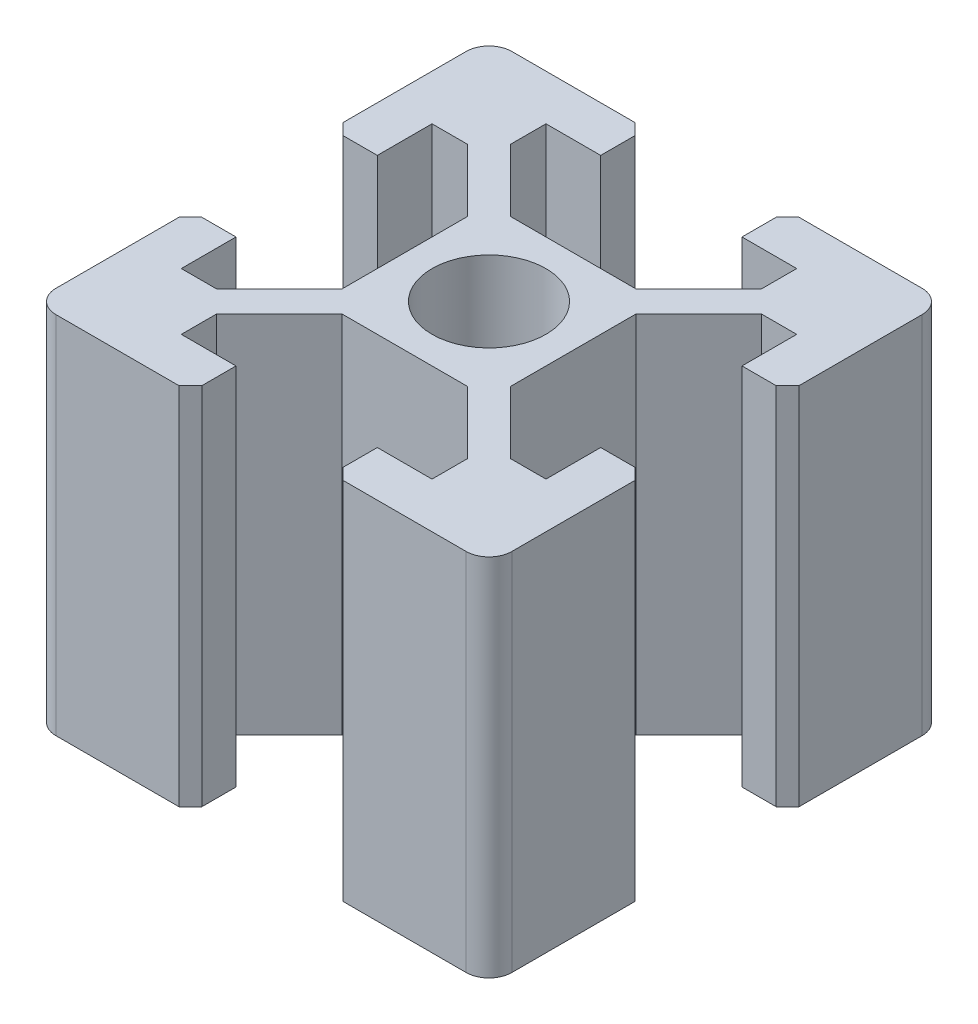
SolidWorks part; units mm, degrees
ref_plane "Front Plane" through (0, 0, 0) normal (0, 0, 1) x (1, 0, 0)
ref_plane "Top Plane" through (0, 0, 0) normal (0, 1, 0) x (1, 0, 0)
ref_plane "Right Plane" through (0, 0, 0) normal (1, 0, 0) x (0, 0, -1)
sketch "Sketch1" plane through (0, 0, 0) normal (0, 1, 0) x (1, 0, 0)
  line L0 (3.6, 10) -> (9, 10)
  line L1 (-9, -10) -> (-3.6, -10)
  line L2 (-10, -9) -> (-10, -3.6)
  line L3 (-9, 10) -> (-3.6, 10)
  line L4 (10, -9) -> (10, -3.6)
  line L5 (-10, -10) -> (10, 10) construction
  line L6 (-10, 10) -> (10, -10) construction
  line L8 (-3.1, 9.5) -> (-3.1, 8)
  line L10 (3.1, 9.5) -> (3.1, 8)
  line L11 (-3.6, 10) -> (-3.1, 9.5)
  line L12 (3.1, 9.5) -> (3.6, 10)
  line L13 (3.1, 8) -> (5.5, 8)
  line L14 (-5.5, 8) -> (-3.1, 8)
  line L15 (-5.5, 8) -> (-5.5, 6.45)
  line L16 (-2.75, 3.7) -> (2.75, 3.7)
  line L17 (5.5, 8) -> (5.5, 6.45)
  line L18 (-5.5, 6.45) -> (-2.75, 3.7)
  line L19 (2.75, 3.7) -> (5.5, 6.45)
  line L20 (3.7, 2.75) -> (6.45, 5.5)
  line L21 (6.45, -5.5) -> (3.7, -2.75)
  line L22 (8, 5.5) -> (6.45, 5.5)
  line L23 (3.7, -2.75) -> (3.7, 2.75)
  line L24 (8, -5.5) -> (6.45, -5.5)
  line L25 (8, -5.5) -> (8, -3.1)
  line L26 (8, 3.1) -> (8, 5.5)
  line L27 (9.5, 3.1) -> (10, 3.6)
  line L28 (10, -3.6) -> (9.5, -3.1)
  line L29 (9.5, 3.1) -> (8, 3.1)
  line L30 (9.5, -3.1) -> (8, -3.1)
  line L31 (10, 3.6) -> (10, 9)
  line L32 (-6.45, 5.5) -> (-3.7, 2.75)
  line L33 (-8, 5.5) -> (-6.45, 5.5)
  line L34 (-8, 5.5) -> (-8, 3.1)
  line L35 (-10, 3.6) -> (-9.5, 3.1)
  line L36 (-9.5, 3.1) -> (-8, 3.1)
  line L37 (-10, 9) -> (-10, 3.6)
  line L38 (3.1, -9.5) -> (3.1, -8)
  line L39 (-3.1, -9.5) -> (-3.1, -8)
  line L40 (3.6, -10) -> (3.1, -9.5)
  line L41 (-3.1, -9.5) -> (-3.6, -10)
  line L42 (5.5, -8) -> (3.1, -8)
  line L43 (5.5, -8) -> (5.5, -6.45)
  line L44 (2.75, -3.7) -> (-2.75, -3.7)
  line L45 (5.5, -6.45) -> (2.75, -3.7)
  line L46 (9, -10) -> (3.6, -10)
  line L47 (-3.6, -10) -> (-10, -10)
  line L48 (-3.1, -8) -> (-5.5, -8)
  line L49 (-5.5, -8) -> (-5.5, -6.45)
  line L50 (-2.75, -3.7) -> (-5.5, -6.45)
  line L51 (-3.7, -2.75) -> (-6.45, -5.5)
  line L52 (-8, -5.5) -> (-6.45, -5.5)
  line L53 (-3.7, 2.75) -> (-3.7, -2.75)
  line L54 (-8, -3.1) -> (-8, -5.5)
  line L55 (-9.5, -3.1) -> (-10, -3.6)
  line L56 (-9.5, -3.1) -> (-8, -3.1)
  line L57 (-10, -3.6) -> (-10, -10)
  line L58 (-10, 3.6) -> (-10, 10)
  line L59 (3.6, -10) -> (10, -10)
  circle A0 centre (0, 0) radius 2.5
  arc A1 (-9, -10) -> (-10, -9) centre (-9, -9) cw
  arc A2 (9, -10) -> (10, -9) centre (9, -9) ccw
  arc A3 (9, 10) -> (10, 9) centre (9, 9) cw
  arc A4 (-10, 9) -> (-9, 10) centre (-9, 9) cw
  point P7 (-3.1, 10)
  point P10 (3.1, 10)
  point P16 (5.5, 3.7)
  point P17 (-5.5, 3.7)
  point P35 (3.7, -5.5)
  point P36 (3.7, 5.5)
  point P37 (10, 3.1)
  point P38 (10, -3.1)
  point P39 (-23.4166, 12.409)
  point P46 (-3.7, 5.5)
  point P47 (-10, 3.1)
  point P58 (3.1, -10)
  point P59 (-3.1, -10)
  point P60 (5.5, -3.7)
  point P69 (-5.5, -3.7)
  point P70 (-3.7, -5.5)
  point P71 (-10, -3.1)
  point P72 (-12.5542, 20.1884)
  dimension "D1" = 5
  dimension "D2" = 1
  dimension "D3" = 20
  dimension "D4" = 6.2
  dimension "D5" = 11
  dimension "D6" = 2
  dimension "D7" = 4.3
extrude "Boss-Extrude1" add sketch "Sketch1" along normal blind 16 contours L56 L55 L2 L1 L41 L39 L48 L49 L50 L44 L45 L43 L42 L38 L40 L46 L4 L28 L30 L25 L24 L21 L23 L20 L22 L26 L29 L27 L31 L0 L12 L10 L13 L17 L19 L16 L18 L15 L14 L8 L11 L3 L37 L35 L36 L34 L33 L32 L53 L51 L52
